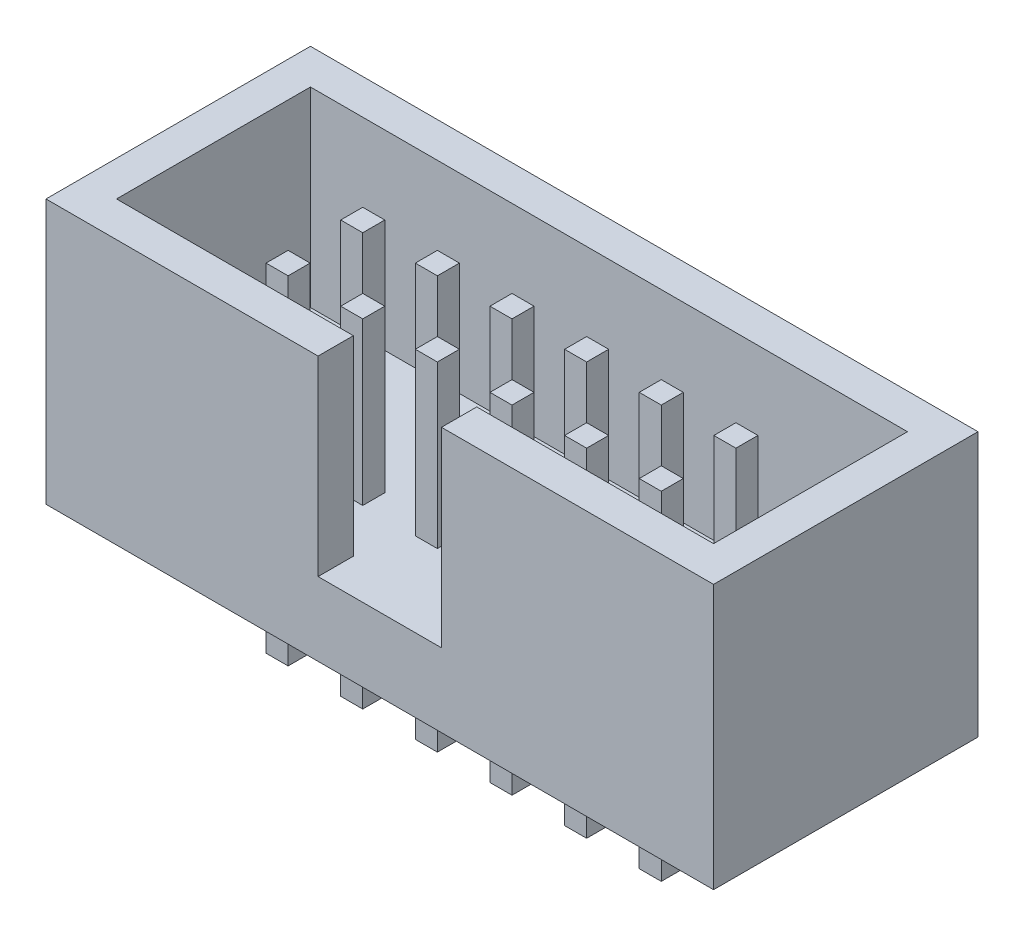
SolidWorks part; units mm, degrees
ref_plane "前视基准面" through (0, 0, 0) normal (0, 0, 1) x (1, 0, 0)
ref_plane "上视基准面" through (0, 0, 0) normal (0, 1, 0) x (1, 0, 0)
ref_plane "右视基准面" through (0, 0, 0) normal (1, 0, 0) x (0, 0, -1)
sketch "草图1" plane through (0, 0, 0) normal (0, 1, 0) x (1, 0, 0)
  line L0 (0, 85.0964) -> (0, -118.2031) construction
  line L1 (-11.36, 4.5) -> (11.36, 4.5)
  line L2 (-11.36, 4.5) -> (-11.36, -4.5)
  line L3 (-11.36, -4.5) -> (11.36, -4.5)
  line L4 (11.36, 4.5) -> (11.36, -4.5)
  line L5 (-200.5452, 0) -> (261.2352, 0) construction
  dimension "D1" = 9
  dimension "D2" = 22.72
extrude "拉伸1" add sketch "草图1" along normal blind 9
sketch "草图2" plane through (0, 9, 0) normal (0, 1, 0) x (-1, 0, 0)
  line L8 (-10.16, 3.3) -> (-10.16, -3.3)
  line L9 (10.16, 3.3) -> (-10.16, 3.3)
  line L10 (10.16, -3.3) -> (10.16, 3.3)
  line L11 (-10.16, -3.3) -> (10.16, -3.3)
  line L12 (-10.16, 3.3) -> (-10.16, -3.3)
  line L13 (10.16, 3.3) -> (-10.16, 3.3)
  line L14 (10.16, -3.3) -> (10.16, 3.3)
  line L15 (-10.16, -3.3) -> (10.16, -3.3)
  dimension "D1" = 1.2
extrude "切除-拉伸1" cut sketch "草图2" against normal blind 6.5
sketch "草图3" plane through (0, 0, 4.5) normal (0, 0, 1) x (1, 0, 0)
  line L0 (-11.36, 9) -> (11.36, 9) construction
  line L1 (-2.1, 9) -> (2.1, 9)
  line L2 (-2.1, 9) -> (-2.1, 2.5)
  line L3 (-2.1, 2.5) -> (2.1, 2.5)
  line L4 (2.1, 9) -> (2.1, 2.5)
  line L5 (-10.16, 2.5) -> (10.16, 2.5) construction
  line L6 (0, 9.4226) -> (0, -4.0288) construction
  dimension "D1" = 4.2
extrude "切除-拉伸2" cut sketch "草图3" against normal blind 6.5
sketch "草图5" plane through (0, 0, 0) normal (0, -1, 0) x (1, 0, 0)
  line L0 (0, 6.0683) -> (0, -6.9786) construction
  line L1 (-14.7999, 0) -> (15.2382, 0) construction
  line L2 (-1.27, 2.5244) -> (-1.27, -0.4442) construction
  line L3 (-1.645, 0.895) -> (-0.895, 0.895)
  line L4 (-1.645, 0.895) -> (-1.645, 1.645)
  line L5 (-1.645, 1.645) -> (-0.895, 1.645)
  line L6 (-0.895, 0.895) -> (-0.895, 1.645)
  line L7 (-2.3518, 1.27) -> (0.5396, 1.27) construction
  line L8 (-4.185, 0.895) -> (-3.435, 0.895)
  line L9 (-4.185, 0.895) -> (-4.185, 1.645)
  line L10 (-4.185, 1.645) -> (-3.435, 1.645)
  line L11 (-3.435, 0.895) -> (-3.435, 1.645)
  line L12 (-6.725, 0.895) -> (-5.975, 0.895)
  line L13 (-6.725, 0.895) -> (-6.725, 1.645)
  line L14 (-6.725, 1.645) -> (-5.975, 1.645)
  line L15 (-5.975, 0.895) -> (-5.975, 1.645)
  line L24 (-5.975, -0.895) -> (-5.975, -1.645)
  line L25 (-6.725, -1.645) -> (-5.975, -1.645)
  line L26 (-6.725, -0.895) -> (-6.725, -1.645)
  line L27 (-6.725, -0.895) -> (-5.975, -0.895)
  line L28 (-3.435, -0.895) -> (-3.435, -1.645)
  line L29 (-4.185, -1.645) -> (-3.435, -1.645)
  line L30 (-4.185, -0.895) -> (-4.185, -1.645)
  line L31 (-4.185, -0.895) -> (-3.435, -0.895)
  line L32 (-0.895, -0.895) -> (-0.895, -1.645)
  line L33 (-1.645, -1.645) -> (-0.895, -1.645)
  line L34 (-1.645, -0.895) -> (-1.645, -1.645)
  line L35 (-1.645, -0.895) -> (-0.895, -0.895)
  line L36 (1.27, 2.5244) -> (1.27, -0.4442) construction
  line L37 (1.645, -0.895) -> (0.895, -0.895)
  line L38 (1.645, -0.895) -> (1.645, -1.645)
  line L39 (1.645, -1.645) -> (0.895, -1.645)
  line L40 (0.895, -0.895) -> (0.895, -1.645)
  line L41 (4.185, -0.895) -> (3.435, -0.895)
  line L42 (4.185, -0.895) -> (4.185, -1.645)
  line L43 (4.185, -1.645) -> (3.435, -1.645)
  line L44 (3.435, -0.895) -> (3.435, -1.645)
  line L45 (6.725, -0.895) -> (5.975, -0.895)
  line L46 (6.725, -0.895) -> (6.725, -1.645)
  line L47 (6.725, -1.645) -> (5.975, -1.645)
  line L48 (5.975, -0.895) -> (5.975, -1.645)
  line L57 (5.975, 0.895) -> (5.975, 1.645)
  line L58 (6.725, 1.645) -> (5.975, 1.645)
  line L59 (6.725, 0.895) -> (6.725, 1.645)
  line L60 (6.725, 0.895) -> (5.975, 0.895)
  line L61 (3.435, 0.895) -> (3.435, 1.645)
  line L62 (4.185, 1.645) -> (3.435, 1.645)
  line L63 (4.185, 0.895) -> (4.185, 1.645)
  line L64 (4.185, 0.895) -> (3.435, 0.895)
  line L65 (0.895, 0.895) -> (0.895, 1.645)
  line L66 (1.645, 1.645) -> (0.895, 1.645)
  line L67 (1.645, 0.895) -> (1.645, 1.645)
  line L68 (1.645, 0.895) -> (0.895, 0.895)
  dimension "D1" = 0.75
  dimension "D2" = 0.75
  dimension "D3" = 1.27
  dimension "D4" = 1.27
extrude "拉伸2" add sketch "草图5" along normal blind 3.5 and the other way offset from surface (8 mm away) 1 other way up to face at (0, 9, 1.3)
sketch "草图6" plane through (0, 0, 0) normal (0, -1, 0) x (1, 0, 0)
  line L0 (14.8773, 0) -> (-15.139, 0) construction
  line L1 (0, 6.7624) -> (0, -6.108) construction
  line L3 (-5.975, 1.645) -> (-6.725, 1.645) construction
  line L4 (-6.725, 1.645) -> (-6.725, 0.895) construction
  line L5 (-6.725, 0.895) -> (-5.975, 0.895) construction
  circle A0 centre (-6.35, 1.27) radius 0.375
